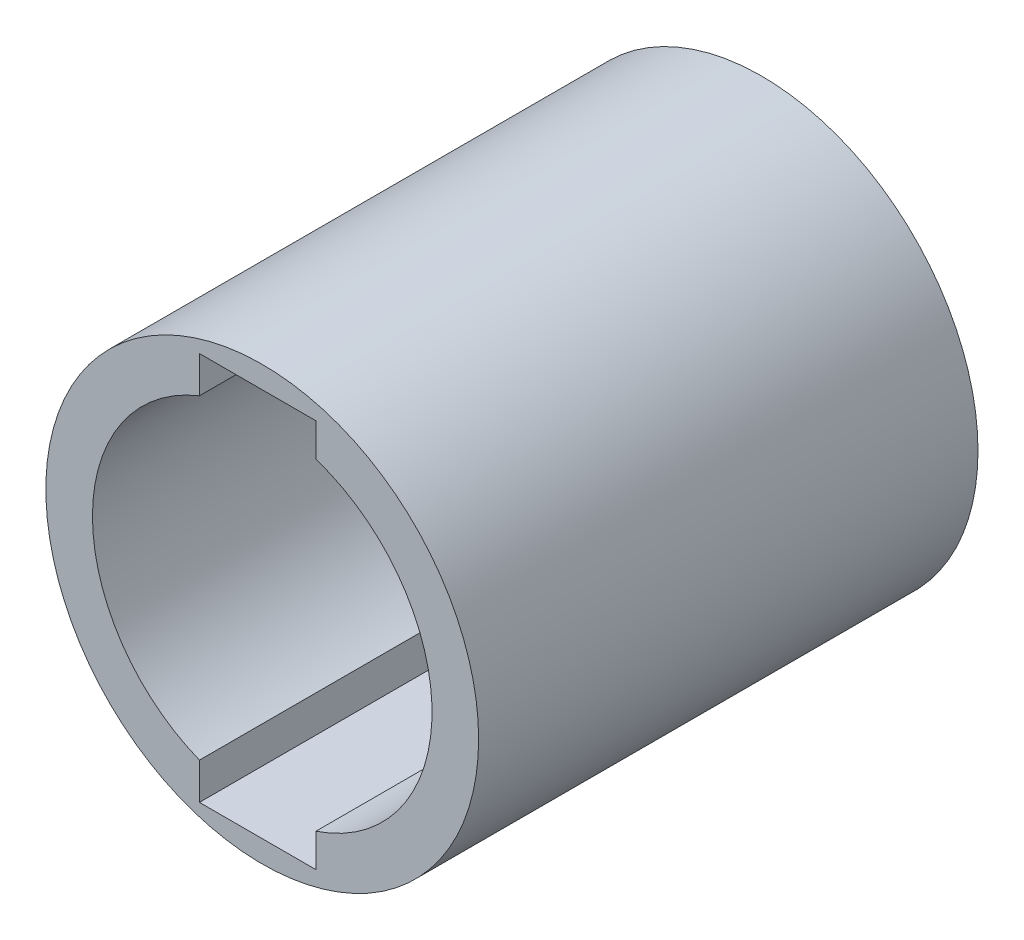
SolidWorks part; units mm, degrees
ref_plane "Front Plane" through (0, 0, 0) normal (1, 0, 0) x (0, 1, 0)
ref_plane "Top Plane" through (0, 0, 0) normal (0, 0, 1) x (0, 1, 0)
ref_plane "Right Plane" through (0, 0, 0) normal (0, 1, 0) x (-1, 0, 0)
sketch "Sketch1" plane through (0, 0, 0) normal (0, 0, 1) x (0, 1, 0)
  circle A0 centre (0, 0) radius 6.5
  dimension "D1" = 13
extrude "Boss-Extrude1" add sketch "Sketch1" along normal blind 15
sketch "Sketch2" plane through (0, 0, 15) normal (0, 0, 1) x (1, 0, 0)
  line L0 (-1.8863, 4.7383) -> (-1.8863, 5.8383)
  line L1 (-1.8863, -5.8383) -> (1.6126, -5.8383)
  line L2 (-1.8863, -5.8383) -> (-1.8863, -4.7383)
  line L3 (-1.8863, 5.8383) -> (1.6126, 5.8383)
  line L4 (1.6126, -5.8383) -> (1.6126, -4.8383)
  line L5 (1.6126, 4.8383) -> (1.6126, 5.8383)
  arc A0 (1.6126, -4.8383) -> (1.6126, 4.8383) centre (0, 0) ccw
  arc A1 (-1.8863, 4.7383) -> (-1.8863, -4.7383) centre (0, 0) ccw
  point P9 (0, 0)
  dimension "D2" = 5.1
  dimension "D1" = 1
  dimension "D3" = 1.1
  dimension "D4" = 1.1
extrude "Cut-Extrude1" cut sketch "Sketch2" against normal through all
